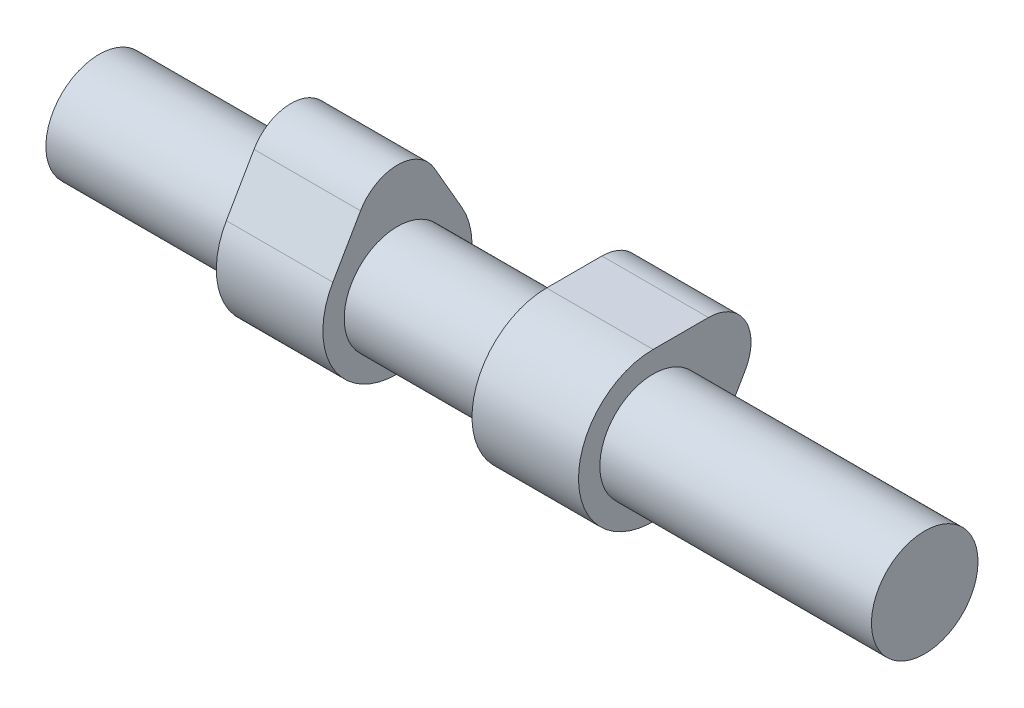
SolidWorks part; units mm, degrees
material "AISI 8620 Steel, carburized"
ref_plane "Front Plane" through (0, 0, 0) normal (1, 0, 0) x (0, 1, 0)
ref_plane "Top Plane" through (0, 0, 0) normal (0, 0, 1) x (0, 1, 0)
ref_plane "Right Plane" through (0, 0, 0) normal (0, 1, 0) x (-1, 0, 0)
sketch "Sketch2" plane through (0, 0, 0) normal (1, 0, 0) x (0, 1, 0)
  line L0 (0, 8.9823) -> (0, -9.7637) construction
  line L1 (-8.1935, 0) -> (15.3626, 0) construction
  line L2 (0, 0) -> (8.7106, -15.0871) construction
  line L3 (-3.5, -6.0622) -> (1, -8.6603)
  line L4 (7, 0) -> (7, -5.1962)
  arc A0 (7, 0) -> (-3.5, -6.0622) centre (0, 0) ccw
  circle A2 centre (0, 0) radius 5
  arc A3 (1, -8.6603) -> (7, -5.1962) centre (3, -5.1962) ccw
  dimension "D1" = 14
  dimension "D2" = 8
  dimension "D4" = 10
  dimension "D3" = 60
  dimension "D5" = 6
extrude "Boss-Extrude1" add sketch "Sketch2" against normal blind 10 contours L3 A3 L4 A0 A2
move or copy body "Body-Move/Copy1" bodies to move or copy 101 copy yes number of copies 1 translate (-24, 0, 0) parameters "D1"=24, "D2"=0, "D3"=0
move or copy body "Body-Move/Copy2" bodies to move or copy 102 copy no rotation origin (0, 0, 0) rotation axis (1, 0, 0) rotation angle 60
sketch "Sketch3" plane through (0, 0, 0) normal (1, 0, 0) x (0, 1, 0)
  circle A0 centre (0, 0) radius 5 construction
  circle A1 centre (0, 0) radius 5
extrude "Boss-Extrude2" add sketch "Sketch3" against normal blind 80 from offset 28
ref_plane "Plane1" through (-12, 0, 0) normal (-1, 0, 0) x (0, -1, 0)
ref_plane "Plane2" through (-5, 0, 0) normal (1, 0, 0) x (0, 1, 0)
ref_plane "Plane3" through (-29, 0, 0) normal (-1, 0, 0) x (0, -1, 0)
sketch "Sketch4" plane through (28, 0, 0) normal (1, 0, 0) x (0, 1, 0)
  circle A1 centre (0, 0) radius 5
  circle A2 centre (0, 0) radius 5
  dimension "D1" = 0
extrude "Cut-Extrude1" cut sketch "Sketch4" against normal blind 2.5
